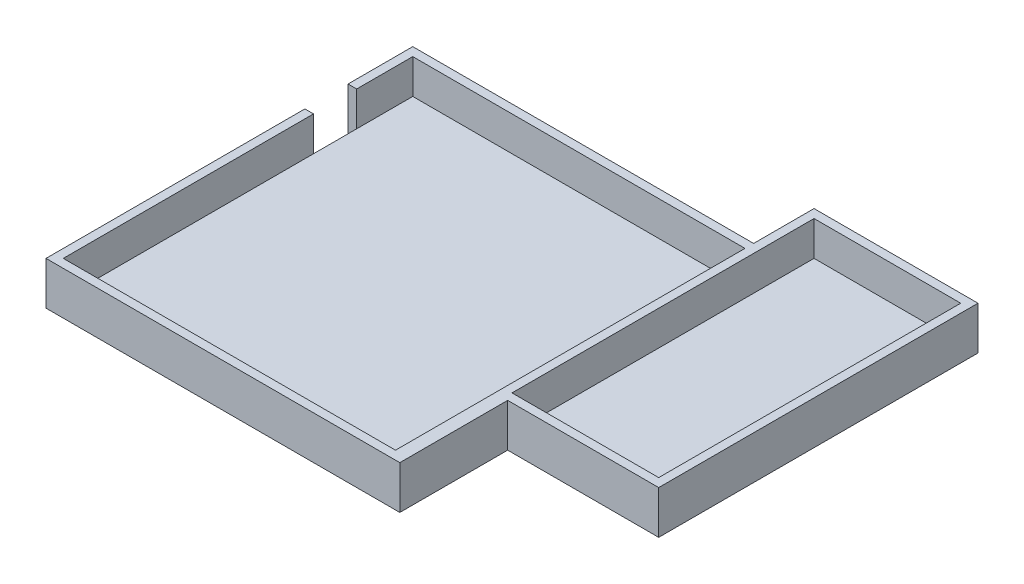
SolidWorks part; units mm, degrees
ref_plane "Front Plane" through (0, 0, 0) normal (0, 0, 1) x (1, 0, 0)
ref_plane "Top Plane" through (0, 0, 0) normal (0, 1, 0) x (1, 0, 0)
ref_plane "Right Plane" through (0, 0, 0) normal (1, 0, 0) x (0, 0, -1)
sketch "Sketch1" plane through (0, 0, 0) normal (0, 1, 0) x (1, 0, 0)
  line L1 (-59.5, -52) -> (59.5, -52)
  line L2 (-59.5, -52) -> (-59.5, 52)
  line L3 (-59.5, 52) -> (59.5, 52)
  line L4 (59.5, -52) -> (59.5, 52)
  line L5 (-59.5, -52) -> (59.5, 52) construction
  line L6 (-59.5, 52) -> (59.5, -52) construction
  point P0 (0, 0)
  dimension "D1" = 104
  dimension "D2" = 119
extrude "Boss-Extrude1" add sketch "Sketch1" along normal blind 10
sketch "Sketch2" plane through (0, 10, 0) normal (0, 1, 0) x (1, 0, 0)
  line L1 (59.5, -52) -> (24.5, -52)
  line L2 (59.5, -52) -> (59.5, -27)
  line L3 (59.5, -27) -> (24.5, -27)
  line L4 (24.5, -52) -> (24.5, -27)
  dimension "D1" = 25
  dimension "D2" = 35
extrude "Cut-Extrude1" cut sketch "Sketch2" against normal through all
sketch "Sketch3" plane through (0, 10, 0) normal (0, 1, 0) x (1, 0, 0)
  line L0 (59.5, -27) -> (59.5, 52) construction
  line L1 (57.5, -25) -> (23.5, -25)
  line L2 (57.5, -25) -> (57.5, 45)
  line L3 (57.5, 45) -> (23.5, 45)
  line L4 (23.5, -25) -> (23.5, 45)
  line L5 (59.5, -27) -> (24.5, -27) construction
  dimension "D1" = 2
  dimension "D2" = 2
  dimension "D3" = 34
  dimension "D4" = 70
extrude "Cut-Extrude2" cut sketch "Sketch3" against normal blind 8
sketch "Sketch4" plane through (0, 10, 0) normal (0, 1, 0) x (1, 0, 0)
  line L1 (-55.5, 31) -> (21.5, 31)
  line L2 (-55.5, 31) -> (-55.5, -50)
  line L3 (-55.5, -50) -> (21.5, -50)
  line L4 (21.5, 31) -> (21.5, -50)
  line L5 (-59.5, -52) -> (24.5, -52) construction
  line L6 (23.5, 45) -> (23.5, -25) construction
  dimension "D1" = 81
  dimension "D2" = 77
  dimension "D3" = 2
  dimension "D4" = 2
extrude "Cut-Extrude3" cut sketch "Sketch4" against normal blind 8
sketch "Sketch5" plane through (0, 10, 0) normal (0, 1, 0) x (1, 0, 0)
  line L0 (-59.5, 52) -> (59.5, 52)
  line L1 (59.5, 52) -> (59.5, 47)
  line L2 (59.5, -27) -> (59.5, 52) construction
  line L3 (59.5, 47) -> (21.5, 47)
  line L4 (21.5, 47) -> (21.5, 33)
  line L5 (21.5, 33) -> (-57.5, 33)
  line L6 (-57.5, 33) -> (-57.5, -52)
  line L7 (-59.5, -52) -> (24.5, -52) construction
  line L8 (-57.5, -52) -> (-59.5, -52)
  line L9 (-59.5, -52) -> (-59.5, 52)
  line L10 (-55.5, 31) -> (-55.5, -50) construction
  line L11 (21.5, 31) -> (-55.5, 31) construction
  line L12 (23.5, 45) -> (23.5, -25) construction
  line L13 (57.5, 45) -> (23.5, 45) construction
  dimension "D1" = 2
  dimension "D2" = 2
  dimension "D3" = 2
  dimension "D4" = 2
extrude "Cut-Extrude4" cut sketch "Sketch5" against normal blind 10
sketch "Sketch7" plane through (-57.5, 0, 0) normal (-1, 0, 0) x (0, 0, 1)
  line L0 (52, 10) -> (-33, 10) construction
  line L1 (-18, 10) -> (-8, 10)
  line L2 (-18, 10) -> (-18, 0)
  line L3 (-18, 0) -> (-8, 0)
  line L4 (-8, 10) -> (-8, 0)
  line L5 (52, 0) -> (-33, 0) construction
  line L6 (-33, 0) -> (-33, 10) construction
  dimension "D1" = 15
  dimension "D2" = 25
extrude "Cut-Extrude6" cut sketch "Sketch7" against normal blind 2
